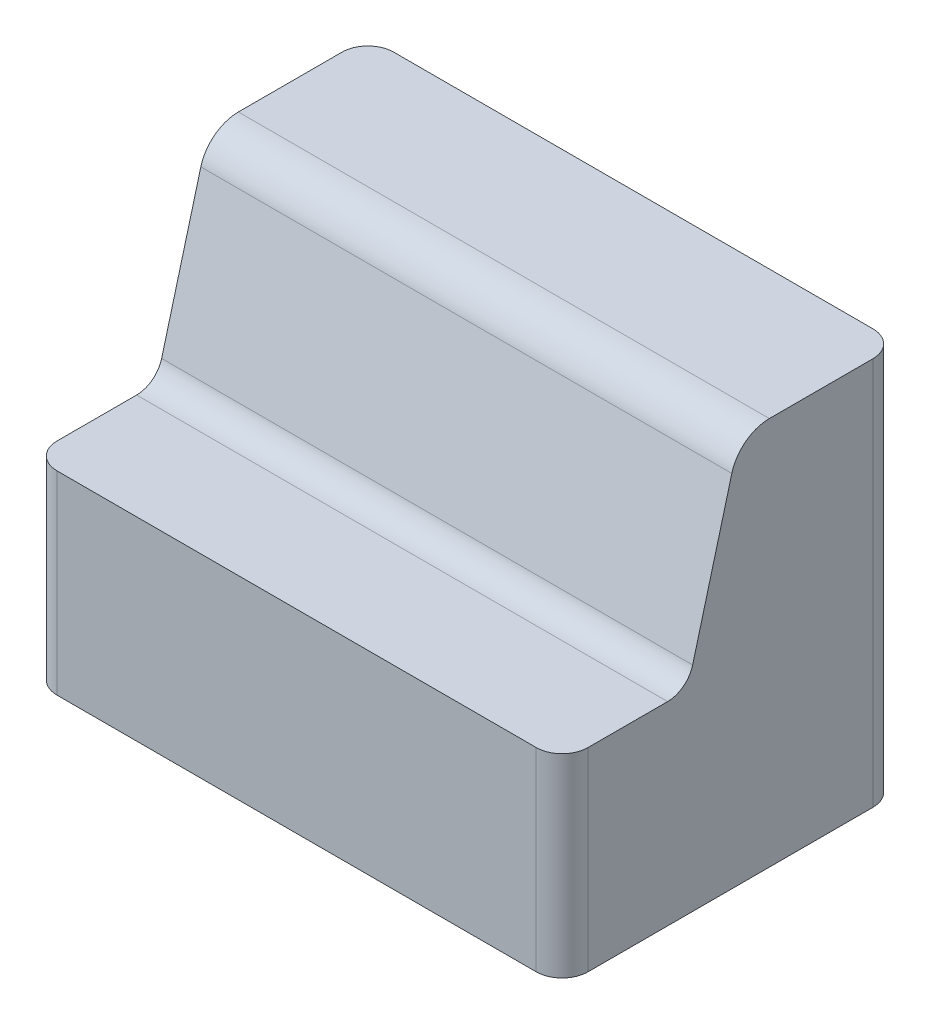
SolidWorks part; units mm, degrees
material "K110"
ref_plane "Front Plane" through (0, 0, 0) normal (0, 0, 1) x (1, 0, 0)
ref_plane "Top Plane" through (0, 0, 0) normal (0, 1, 0) x (1, 0, 0)
ref_plane "Right Plane" through (0, 0, 0) normal (1, 0, 0) x (0, 0, -1)
sketch "Sketch1" plane through (0, 0, 0) normal (1, 0, 0) x (0, 0, -1)
  line L0 (-10, 0) -> (0, 0)
  line L1 (0, 0) -> (0, -30)
  line L2 (0, -30) -> (-26, -30)
  line L3 (-26, -30) -> (-26, -15)
  line L4 (-26, -15) -> (-16.3212, -15)
  line L5 (-16.3212, -15) -> (-12.8978, -2.2235)
  arc A0 (-12.8978, -2.2235) -> (-10, 0) centre (-10, -3) cw
  dimension "D2" = 3
  dimension "D1" = 10
  dimension "D3" = 30
  dimension "D4" = 15
  dimension "D5" = 75
  dimension "D6" = 26
extrude "Boss-Extrude1" add sketch "Sketch1" along normal mid plane 41
fillet "Fillet1" radius 2 4 edges at (-20.5, -15, 0) (-20.5, -22.5, 26) (20.5, -15, 0) (20.5, -22.5, 26)
hole_wizard "M6 Tapped Hole1" positions "Sketch5" profile "Sketch3" tap size "M6" standard "ISO"
sketch "Sketch5" plane through (0, -30, 0) normal (0, -1, 0) x (-1, 0, 0)
  line L0 (-18.5, 0) -> (18.5, 0) construction
  line L1 (-20.5, -24) -> (-20.5, -2) construction
  line L2 (20.5, -24) -> (20.5, -2) construction
  point P0 (-13, -7.5)
  point P2 (13, -7.5)
  point P12 (0, 0)
  dimension "D1" = 7.5
  dimension "D2" = 7.5
  dimension "D3" = 7.5
sketch "Sketch3" plane through (13, -30, 7.5) normal (1, 0, 0) x (0, 0, -1)
  line L0 (0, 0) -> (0, 18.5022)
  line L1 (0, 18.5022) -> (2.5, 17)
  line L2 (2.5, 17) -> (2.5, 0.525)
  line L3 (2.5, 0.525) -> (3.025, 0)
  line L5 (3.025, 0) -> (0, 0)
  line L6 (-2.5, 0.525) -> (-3.025, 0) construction
  line L10 (0, 18.5022) -> (-2.5, 17) construction
  line L11 (0, -6.35) -> (0, 107.95) construction
  dimension "Tap Drill Dia." = 5
  dimension "Tap Drill Depth" = 17
  dimension "Near C'Sink Dia." = 6.05
  dimension "Near C'Sink Angle" = 90
  dimension "Drill Angle" = 118
cosmetic thread "Hole Thread1" parameters "D1"=12, "D2"=6
cosmetic thread "Hole Thread2" parameters "D1"=12, "D2"=6
fillet "Fillet2" radius 2 1 edges at (0, -15, 16.3212)
